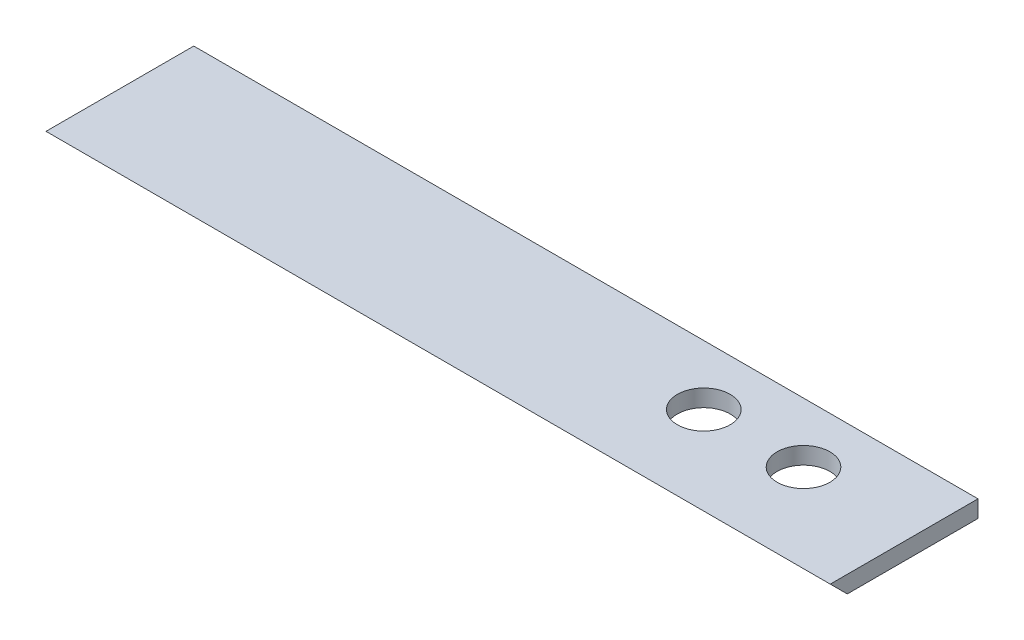
SolidWorks part; units mm, degrees
material "Plywood"
ref_plane "Front Plane" through (0, 0, 0) normal (0, 0, 1) x (1, 0, 0)
ref_plane "Top Plane" through (0, 0, 0) normal (0, 1, 0) x (1, 0, 0)
ref_plane "Right Plane" through (0, 0, 0) normal (1, 0, 0) x (0, 0, -1)
sketch "Sketch1" plane through (0, 0, 0) normal (0, 1, 0) x (1, 0, 0)
  line L1 (-62.8005, 149.2818) -> (813.4995, 149.2818)
  line L2 (-62.8005, 149.2818) -> (-62.8005, -15.8182)
  line L3 (-62.8005, -15.8182) -> (813.4995, -15.8182)
  line L4 (813.4995, 149.2818) -> (813.4995, -15.8182)
extrude "Boss-Extrude1" add sketch "Sketch1" along normal blind 19.05 contours L2 L1 L4 L3
sketch "Sketch2" plane through (0, 19.05, 0) normal (0, 1, 0) x (1, 0, 0)
  circle A0 centre (685.2403, 82.5679) radius 29.5
sketch "Sketch3" plane through (0, 19.05, 0) normal (0, 1, 0) x (1, 0, 0)
  circle A0 centre (573.9059, 82.4588) radius 29.5
extrude "Cut-Extrude1" cut sketch "Sketch3" against normal blind 19.05 contours A0
extrude "Cut-Extrude2" cut sketch "Sketch2" against normal blind 19.05
sketch "Sketch4" plane through (-62.8005, 0, 0) normal (-1, 0, 0) x (0, 0, 1)
  line L0 (-3.2318, 0) -> (15.8182, 19.05)
  line L1 (-149.2818, 0) -> (15.8182, 0) construction
  line L2 (15.8182, 19.05) -> (15.8182, 0)
  line L3 (15.8182, 19.05) -> (15.8182, 0) construction
  line L4 (15.8182, 0) -> (-3.2318, 0)
  dimension "D1" = 45
extrude "Cut-Extrude3" cut sketch "Sketch4" against normal blind 914.4
